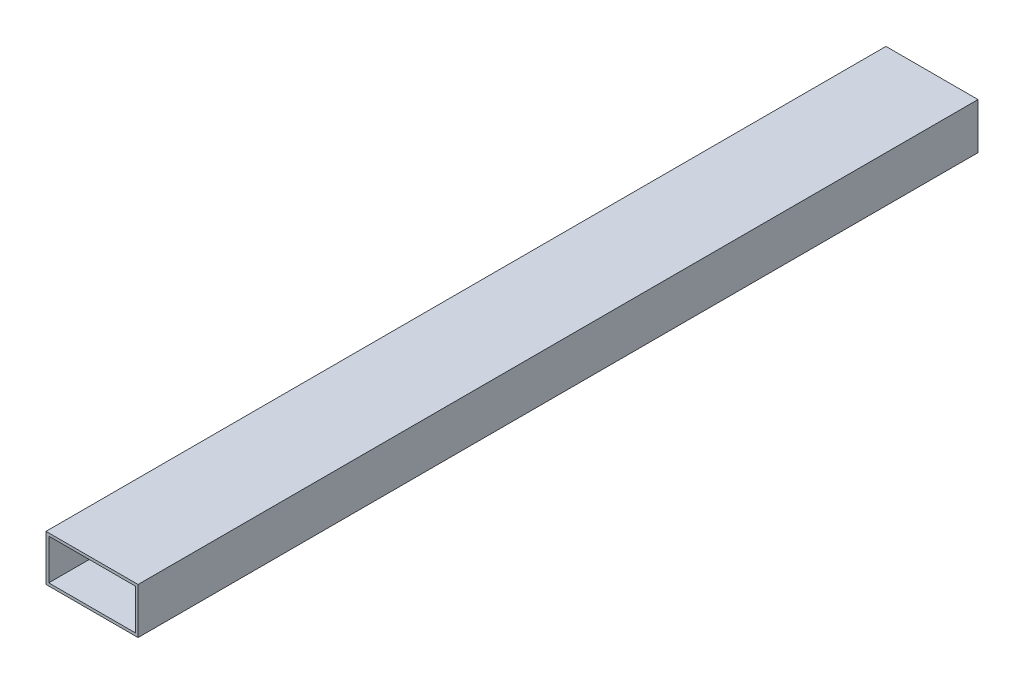
SolidWorks part; units mm, degrees
ref_plane "Front Plane" through (0, 0, 0) normal (0, 0, 1) x (1, 0, 0)
ref_plane "Top Plane" through (0, 0, 0) normal (0, 1, 0) x (1, 0, 0)
ref_plane "Right Plane" through (0, 0, 0) normal (1, 0, 0) x (0, 0, -1)
sketch "Sketch1" plane through (0, 0, 0) normal (0, 0, 1) x (1, 0, 0)
  line L1 (0, 0) -> (-50.8, 0)
  line L2 (0, 0) -> (0, 25.4)
  line L3 (0, 25.4) -> (-50.8, 25.4)
  line L4 (-50.8, 0) -> (-50.8, 25.4)
  dimension "D1" = 50.8
  dimension "D2" = 25.4
extrude "Extrude-Thin1" add sketch "Sketch1" along normal blind 463.55 thin
